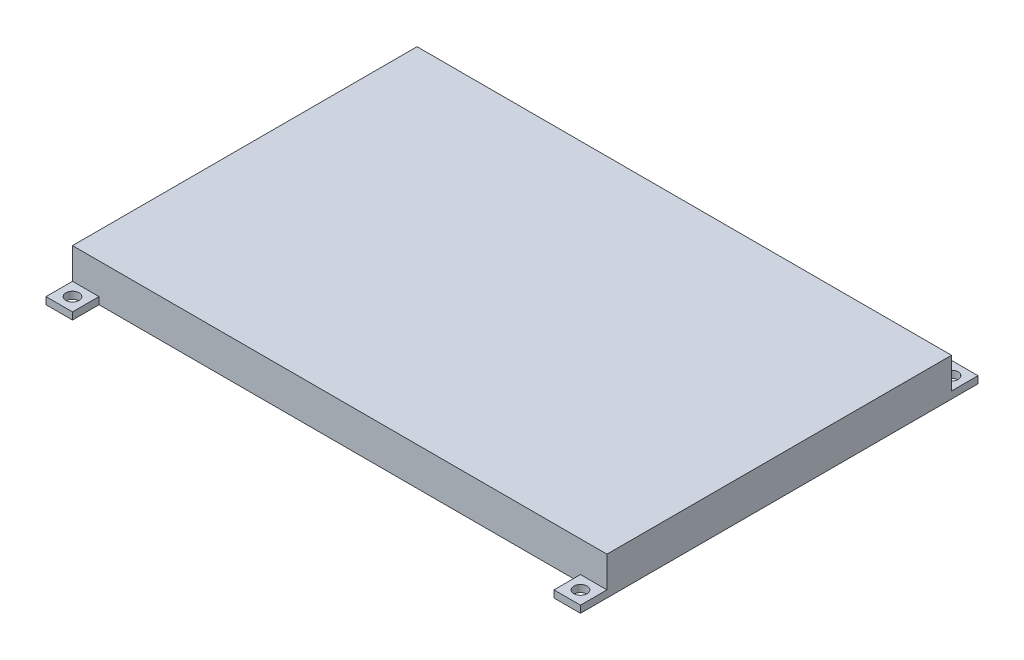
SolidWorks part; units mm, degrees
ref_plane "Front Plane" through (0, 0, 0) normal (0, 0, 1) x (1, 0, 0)
ref_plane "Top Plane" through (0, 0, 0) normal (0, 1, 0) x (1, 0, 0)
ref_plane "Right Plane" through (0, 0, 0) normal (1, 0, 0) x (0, 0, -1)
sketch "Sketch1" plane through (0, 0, 0) normal (0, 1, 0) x (1, 0, 0)
  line L0 (-160.8423, -19.805) -> (-166.8423, -19.805) construction
  line L1 (-166.8423, 58.195) -> (-45.8423, 58.195) construction
  line L2 (-166.8423, 58.195) -> (-166.8423, -19.805)
  line L3 (-166.8423, -19.805) -> (-45.8423, -19.805) construction
  line L4 (-45.8423, 58.195) -> (-45.8423, -19.805)
  line L5 (-166.8423, 58.195) -> (-45.8423, -19.805) construction
  line L6 (-166.8423, -19.805) -> (-45.8423, 58.195) construction
  line L7 (-45.8423, -19.805) -> (-51.8423, -19.805) construction
  line L8 (-45.8423, -19.805) -> (-45.8423, -25.805) construction
  line L9 (-45.8423, -25.805) -> (-51.8423, -25.805) construction
  line L10 (-51.8423, -19.805) -> (-51.8423, -25.805) construction
  line L11 (-160.8423, -19.805) -> (-160.8423, -25.805) construction
  line L12 (-160.8423, -25.805) -> (-166.8423, -25.805) construction
  line L13 (-166.8423, -19.805) -> (-166.8423, -25.805) construction
  line L14 (-160.8423, 64.195) -> (-166.8423, 64.195) construction
  line L15 (-160.8423, 64.195) -> (-160.8423, 58.195) construction
  line L16 (-160.8423, 58.195) -> (-166.8423, 58.195) construction
  line L17 (-166.8423, 64.195) -> (-166.8423, 58.195) construction
  line L18 (-45.8423, 64.195) -> (-51.8423, 64.195) construction
  line L19 (-45.8423, 64.195) -> (-45.8423, 58.195) construction
  line L20 (-45.8423, 58.195) -> (-51.8423, 58.195) construction
  line L21 (-51.8423, 64.195) -> (-51.8423, 58.195) construction
  line L22 (-106.3423, 58.195) -> (-106.3423, -19.805) construction
  line L23 (-166.8423, 58.195) -> (-166.8423, 64.195)
  line L24 (-166.8423, 64.195) -> (-160.8423, 64.195)
  line L26 (-166.8423, 19.195) -> (-45.8423, 19.195) construction
  line L27 (-160.8423, 64.195) -> (-160.8423, 58.195)
  line L28 (-160.8423, 58.195) -> (-51.8423, 58.195)
  line L29 (-51.8423, 58.195) -> (-51.8423, 64.195)
  line L30 (-51.8423, 64.195) -> (-45.8423, 64.195)
  line L31 (-45.8423, 64.195) -> (-45.8423, 58.195)
  line L32 (-45.8423, -19.805) -> (-45.8423, -25.805)
  line L33 (-45.8423, -25.805) -> (-51.8423, -25.805)
  line L34 (-51.8423, -25.805) -> (-51.8423, -19.805)
  line L35 (-51.8423, -19.805) -> (-160.8423, -19.805)
  line L36 (-160.8423, -19.805) -> (-160.8423, -25.805)
  line L37 (-160.8423, -25.805) -> (-166.8423, -25.805)
  line L38 (-166.8423, -25.805) -> (-166.8423, -19.805)
  circle A3 centre (-48.8423, -22.805) radius 1.5
  circle A4 centre (-163.8423, -22.805) radius 1.5
  circle A6 centre (-48.8423, 61.195) radius 1.5
  circle A7 centre (-163.8423, 61.195) radius 1.5
  point P0 (-106.3423, 19.195)
  point P24 (0, 0)
  point P30 (0, 0)
  point P32 (-147.1276, -23.805)
  dimension "D11" = 121
  dimension "D12" = 3
  dimension "D15" = 3
  dimension "D13" = 78
  dimension "D2" = 84
  dimension "D3" = 90
  dimension "D4" = 6
  dimension "D5" = 115
extrude "Boss-Extrude1" add sketch "Sketch1" along normal blind 1.6
sketch "Sketch2" plane through (0, 1.6, 0) normal (0, 1, 0) x (1, 0, 0)
  line L0 (-45.8423, -25.805) -> (-45.8423, 64.195) construction
  line L1 (-166.8423, 58.195) -> (-45.8423, 58.195)
  line L2 (-166.8423, 58.195) -> (-166.8423, -19.805)
  line L3 (-166.8423, -19.805) -> (-45.8423, -19.805)
  line L4 (-45.8423, 58.195) -> (-45.8423, -19.805)
  line L5 (-166.8423, 64.195) -> (-166.8423, -25.805) construction
  line L6 (-51.8423, 58.195) -> (-160.8423, 58.195) construction
  line L7 (-160.8423, -19.805) -> (-51.8423, -19.805) construction
extrude "Boss-Extrude2" add sketch "Sketch2" along normal blind 7
